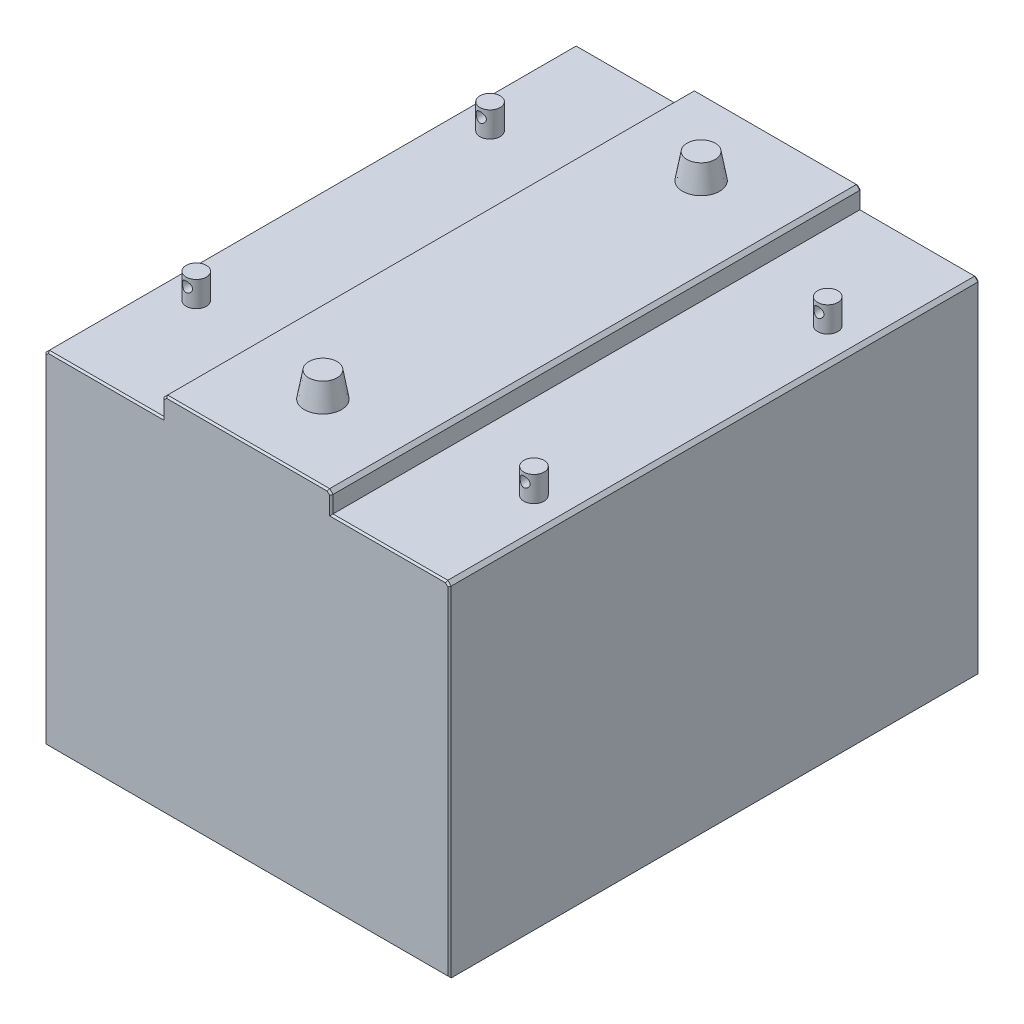
SolidWorks part; units mm, degrees
ref_plane "前视基准面" through (0, 0, 0) normal (0, 0, 1) x (1, 0, 0)
ref_plane "上视基准面" through (0, 0, 0) normal (0, 1, 0) x (1, 0, 0)
ref_plane "右视基准面" through (0, 0, 0) normal (1, 0, 0) x (0, 0, -1)
sketch "草图1" plane through (0, 0, 0) normal (0, 0, 1) x (1, 0, 0)
  line L1 (-120, -107.5) -> (120, -107.5)
  line L2 (-120, -107.5) -> (-120, 107.5)
  line L3 (-120, 107.5) -> (120, 107.5)
  line L4 (120, -107.5) -> (120, 107.5)
  line L5 (-120, -107.5) -> (120, 107.5) construction
  line L6 (-120, 107.5) -> (120, -107.5) construction
  point P0 (0, 0)
  dimension "D1" = 240
  dimension "D2" = 215
extrude "凸台-拉伸1" add sketch "草图1" along normal blind 314
sketch "草图2" plane through (0, 0, 314) normal (0, 0, 1) x (1, 0, 0)
  line L0 (120, -107.5) -> (120, 107.5) construction
  line L1 (-143.9301, 128.9546) -> (-50, 128.9546)
  line L2 (-143.9301, 128.9546) -> (-143.9301, 95.5)
  line L3 (-143.9301, 95.5) -> (-50, 95.5)
  line L4 (-50, 128.9546) -> (-50, 95.5)
  line L5 (50, 125.9437) -> (120, 125.9437)
  line L6 (50, 125.9437) -> (50, 95.5)
  line L7 (50, 95.5) -> (120, 95.5)
  line L8 (120, 125.9437) -> (120, 95.5)
  line L9 (120, 107.5) -> (-120, 107.5) construction
  dimension "D1" = 50
  dimension "D2" = 50
  dimension "D3" = 12
  dimension "D4" = 12
extrude "切除-拉伸1" cut sketch "草图2" against normal through all
chamfer "倒角1" distance 2 angle 45 4 edges at (-120, 95.5, 157) (120, 95.5, 157) (50, 107.5, 157) (-50, 107.5, 157)
sketch "草图3" plane through (0, 95.5, 0) normal (0, 1, 0) x (1, 0, 0)
  line L0 (-50, 0) -> (-118, 0) construction
  line L1 (-118, -314) -> (-50, -314) construction
  line L2 (-120, -314) -> (-120, 0) construction
  circle A0 centre (-100, -70) radius 6
  circle A1 centre (-100, -244) radius 6
  dimension "D1" = 12
  dimension "D2" = 12
  dimension "D3" = 70
  dimension "D4" = 70
  dimension "D5" = 20
  dimension "D6" = 20
extrude "凸台-拉伸2" add sketch "草图3" along normal blind 15
sketch "草图4" plane through (0, 0, 314) normal (0, 0, 1) x (1, 0, 0)
  line L0 (-94, 110.5) -> (-106, 110.5) construction
  circle A0 centre (-100, 105.5) radius 3
  dimension "D1" = 6
  dimension "D2" = 5
extrude "切除-拉伸2" cut sketch "草图4" against normal through all
sketch "草图5" plane through (0, 107.5, 0) normal (0, 1, 0) x (1, 0, 0)
  line L0 (48, 0) -> (-48, 0) construction
  line L1 (48, -314) -> (-48, -314) construction
  circle A0 centre (0, -45) radius 11
  circle A1 centre (0, -269) radius 11
  dimension "D1" = 22
  dimension "D2" = 22
  dimension "D3" = 45
  dimension "D4" = 45
extrude "凸台-拉伸3" add sketch "草图5" along normal blind 15 draft 10
mirror "镜向1" about plane through (0, 0, 0) normal (1, 0, 0) of "凸台-拉伸2", "切除-拉伸2"
chamfer "倒角2" distance 1 angle 45 24 edges at (0, -107.5, 0) (120, -7, 0) (119, 94.5, 0) (84, 95.5, 0) (50, 100.5, 0) (49, 106.5, 0) (0, 107.5, 0) (-49, 106.5, 0) (-50, 100.5, 0) (-84, 95.5, 0) (-119, 94.5, 0) (-120, -7, 0) (-50, 100.5, 314) (-49, 106.5, 314) (0, 107.5, 314) (49, 106.5, 314) (50, 100.5, 314) (84, 95.5, 314) (119, 94.5, 314) (120, -7, 314) (0, -107.5, 314) (-120, -7, 314) (-119, 94.5, 314) (-84, 95.5, 314)
